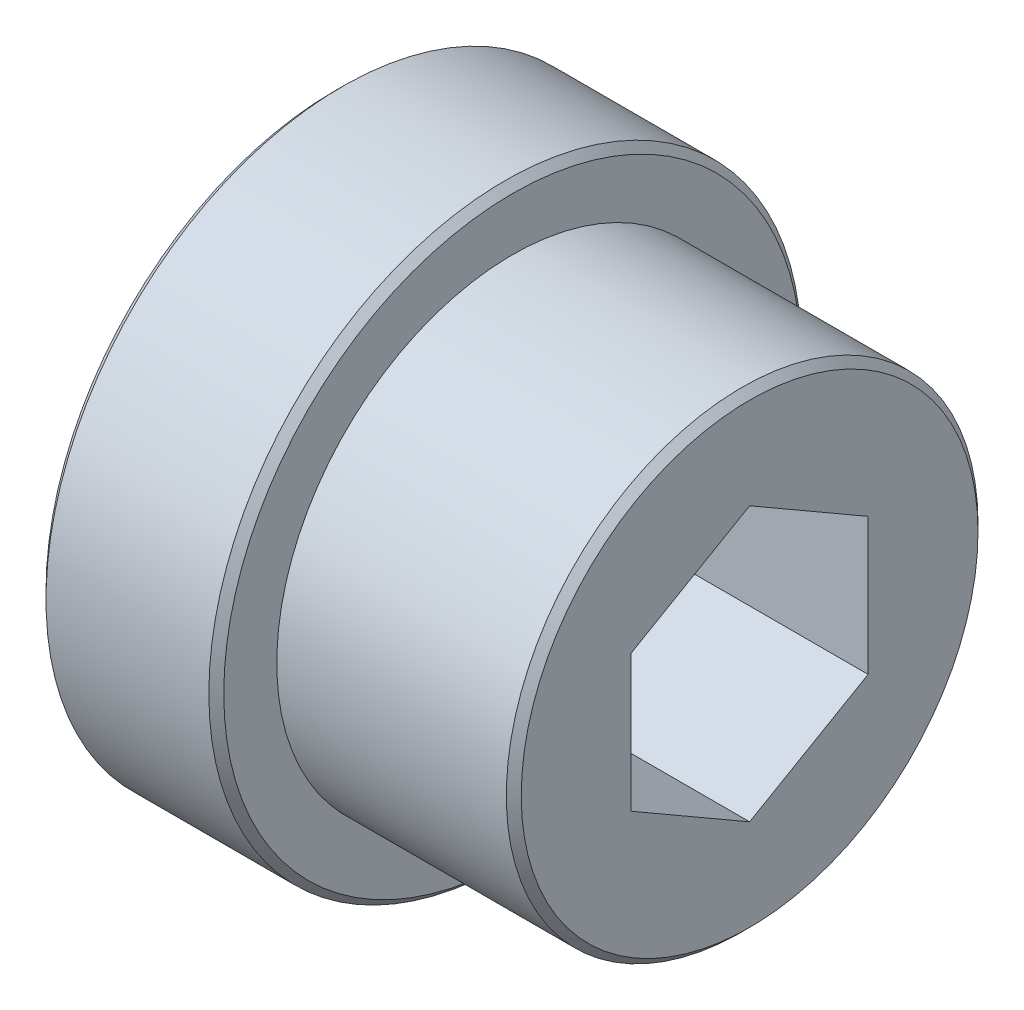
SolidWorks part; units mm, degrees
material "Nylon 101"
ref_plane "Front Plane" through (0, 0, 0) normal (0, 0, 1) x (1, 0, 0)
ref_plane "Top Plane" through (0, 0, 0) normal (0, 1, 0) x (1, 0, 0)
ref_plane "Right Plane" through (0, 0, 0) normal (1, 0, 0) x (0, 0, -1)
sketch "Sketch1" plane through (0, 0, 0) normal (1, 0, 0) x (0, 0, -1)
  circle A0 centre (0, 0) radius 12.6365
  dimension "D1" = 25.273
extrude "Boss-Extrude1" add sketch "Sketch1" along normal blind 12.7
sketch "Sketch2" plane through (0, 0, 0) normal (-1, 0, 0) x (0, 0, 1)
  circle A0 centre (0, 0) radius 15.875
  dimension "D1" = 31.75
extrude "Boss-Extrude2" add sketch "Sketch2" along normal blind 9.525
sketch "Sketch3" plane through (-9.525, 0, 0) normal (-1, 0, 0) x (0, 0, 1)
  circle A0 centre (0, 0) radius 11.1125
  dimension "D1" = 22.225
chamfer "Chamfer1" distance 0.4 angle 45 3 edges at (12.7, 0, -12.6365) (-9.525, 0, 15.875) (0, 0, 15.875)
sketch "Sketch4" plane through (-9.525, 0, 0) normal (-1, 0, 0) x (0, 0, 1)
  line L1 (0, 7.3323) -> (-6.35, 3.6662)
  line L2 (-6.35, 3.6662) -> (-6.35, -3.6662)
  line L3 (-6.35, -3.6662) -> (0, -7.3323)
  line L4 (0, -7.3323) -> (6.35, -3.6662)
  line L5 (6.35, -3.6662) -> (6.35, 3.6662)
  line L6 (6.35, 3.6662) -> (0, 7.3323)
  circle A0 centre (0, 0) radius 6.35 construction
  dimension "D1" = 12.7
extrude "Cut-Extrude1" cut sketch "Sketch4" against normal through all
